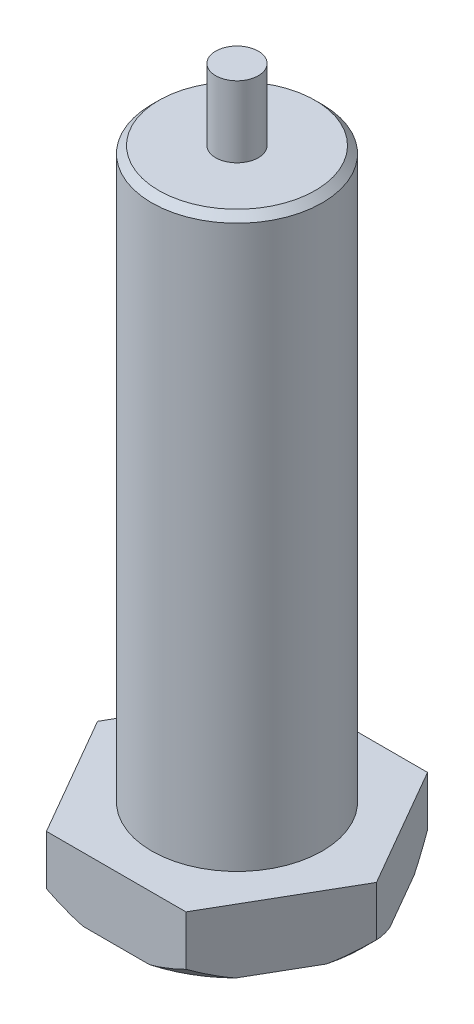
SolidWorks part; units mm, degrees
material "1.0038 (S235JRG2)"
ref_plane "Horní rovina" through (0, 0, 0) normal (0, 0, 1) x (1, 0, 0)
ref_plane "Přední rovina" through (0, 0, 0) normal (0, 1, 0) x (1, 0, 0)
ref_plane "Pravá rovina" through (0, 0, 0) normal (1, 0, 0) x (0, 0, -1)
sketch "Skica1" plane through (0, 0, 0) normal (0, 1, 0) x (1, 0, 0)
  line L1 (9.815, 0) -> (4.9075, 8.5)
  line L2 (4.9075, 8.5) -> (-4.9075, 8.5)
  line L3 (-4.9075, 8.5) -> (-9.815, 0)
  line L4 (-9.815, 0) -> (-4.9075, -8.5)
  line L5 (-4.9075, -8.5) -> (4.9075, -8.5)
  line L6 (4.9075, -8.5) -> (9.815, 0)
  circle A0 centre (0, 0) radius 8.5 construction
  dimension "D1" = 17
extrude "Přidat vysunutím1" add sketch "Skica1" along normal blind 4.5
sketch "Skica2" plane through (0, 4.5, 0) normal (0, 1, 0) x (1, 0, 0)
  circle A0 centre (0, 0) radius 6
  dimension "D1" = 12
extrude "Přidat vysunutím2" add sketch "Skica2" along normal blind 40
sketch "Skica3" plane through (0, 44.5, 0) normal (0, 1, 0) x (1, 0, 0)
  circle A0 centre (0, 0) radius 1.5
  dimension "D1" = 3
extrude "Přidat vysunutím3" add sketch "Skica3" along normal blind 5
sketch "Skica4" plane through (0, 0, 0) normal (0, 0, 1) x (1, 0, 0)
  line L0 (-9.815, 4.5) -> (-9.815, 0) construction
  line L1 (-9.815, 0) -> (-4.9075, 0) construction
  line L2 (-9.815, 4.5) -> (-9.815, 0) construction
  line L3 (-9.815, 0) -> (-4.9075, 0) construction
  line L4 (-9.815, 0.9998) -> (-8.8151, 0)
  line L5 (-9.815, 0.9998) -> (-9.815, 0)
  line L6 (-9.815, 0) -> (-8.8151, 0)
  line L7 (0, 0) -> (0, 9.5242) construction
  dimension "D1" = 1.414
  dimension "D2" = 45
revolve "Odebrat rotací1" cut sketch "Skica4" angle 360 about L7
chamfer "Zkosení1" distance 0.5 angle 45 1 edges at (0, 44.5, 6)
